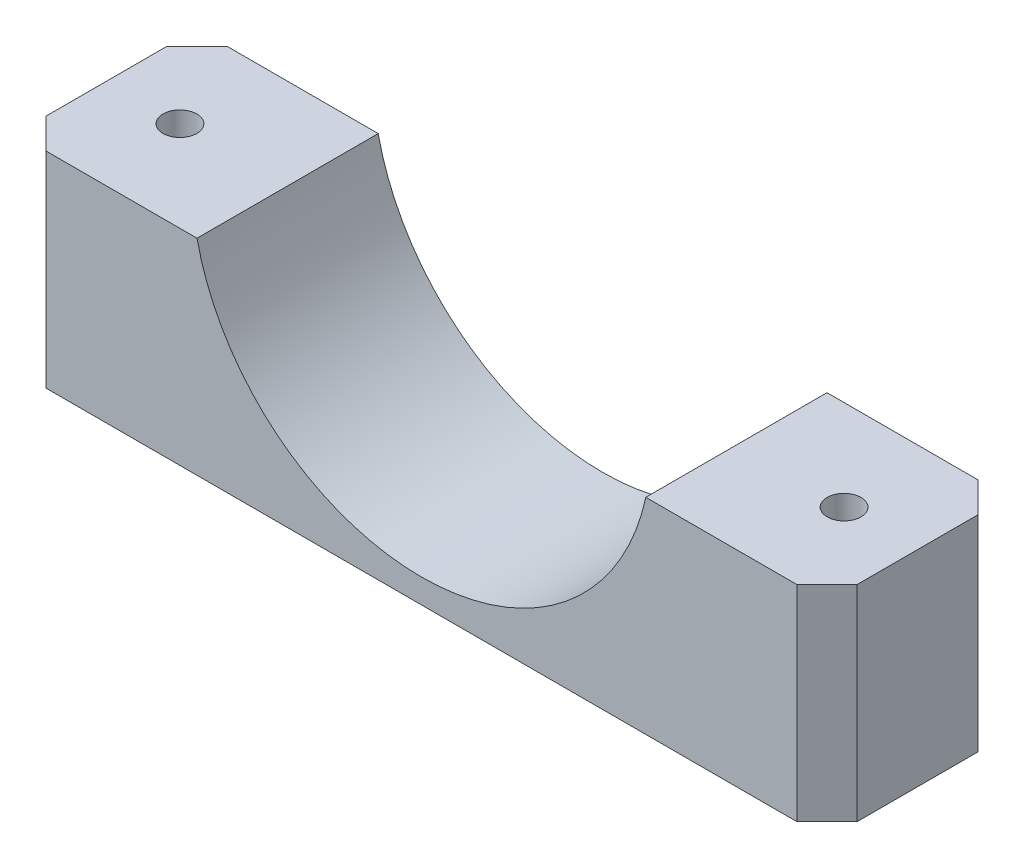
SolidWorks part; units mm, degrees
ref_plane "Front Plane" through (0, 0, 0) normal (0, 0, 1) x (1, 0, 0)
ref_plane "Top Plane" through (0, 0, 0) normal (0, 1, 0) x (1, 0, 0)
ref_plane "Right Plane" through (0, 0, 0) normal (1, 0, 0) x (0, 0, -1)
sketch "Sketch1" plane through (0, 0, 0) normal (0, 0, 1) x (1, 0, 0)
  line L0 (-18.5742, -4) -> (-33.5742, -4)
  line L1 (-33.5742, -4) -> (-33.5742, -21)
  line L2 (-33.5742, -21) -> (33.5742, -21)
  line L3 (33.5742, -21) -> (33.5742, -4)
  line L4 (33.5742, -4) -> (18.5742, -4)
  arc A0 (-18.5742, -4) -> (18.5742, -4) centre (0, 0) ccw
  dimension "D1" = 19
  dimension "D2" = 15
  dimension "D3" = 15
  dimension "D4" = 21
  dimension "D5" = 4
extrude "Boss-Extrude1" add sketch "Sketch1" along normal blind 15 contours L4 A0 L0 L1 L2 L3
chamfer "Chamfer1" distance 2.5 4 edges at (33.5742, -12.5, 0) (33.5742, -12.5, 15) (-33.5742, -12.5, 0) (-33.5742, -12.5, 15)
sketch "Sketch2" plane through (0, -4, 0) normal (0, 1, 0) x (1, 0, 0)
  line L0 (0, -8.25) -> (0, 8.25) construction
  circle A0 centre (27.4886, -7.5) radius 1.4
  circle A1 centre (-27.4886, -7.5) radius 1.4
  dimension "D1" = 2.8
extrude "Cut-Extrude1" cut sketch "Sketch2" against normal through all
